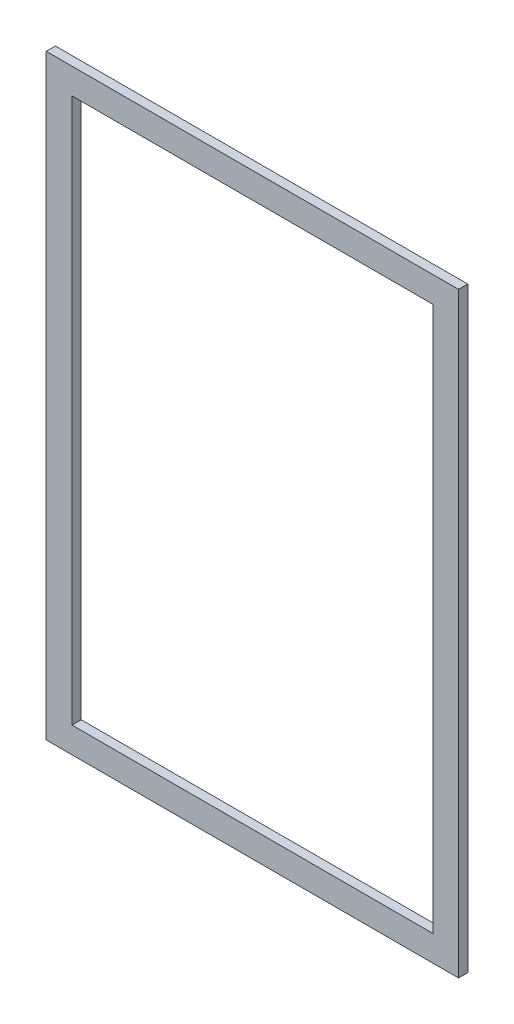
SolidWorks part; units mm, degrees
ref_plane "Front Plane" through (0, 0, 0) normal (0, 0, 1) x (1, 0, 0)
ref_plane "Top Plane" through (0, 0, 0) normal (0, 1, 0) x (1, 0, 0)
ref_plane "Right Plane" through (0, 0, 0) normal (1, 0, 0) x (0, 0, -1)
sketch "Sketch1" plane through (0, 0, 0) normal (0, 0, 1) x (1, 0, 0)
  line L1 (0, 0) -> (224, 0)
  line L2 (0, 0) -> (0, 324)
  line L3 (0, 324) -> (224, 324)
  line L4 (224, 0) -> (224, 324)
  line L6 (14, 14) -> (210, 14)
  line L7 (14, 14) -> (14, 310)
  line L8 (14, 310) -> (210, 310)
  line L9 (210, 14) -> (210, 310)
  dimension "D1" = 14
  dimension "D2" = 210
  dimension "D3" = 224
  dimension "D4" = 14
  dimension "D5" = 310
  dimension "D6" = 324
extrude "Profile" add sketch "Sketch1" along normal blind 5
equation "\"Profile_Depth\" = 5mm"
equation "\"D1@Profile\" = \"Profile_Depth\""
equation "\"Profile_Sketch_1\" = 14mm"
equation "\"D1@Sketch1\" = \"Profile_Sketch_1\""
equation "\"Profile_Sketch_2\" = 210mm"
equation "\"D2@Sketch1\" = \"Profile_Sketch_2\""
equation "\"Profile_Sketch_3\" = 224mm"
equation "\"D3@Sketch1\" = \"Profile_Sketch_3\""
equation "\"Profile_Sketch_4\" = 14mm"
equation "\"D4@Sketch1\" = \"Profile_Sketch_4\""
equation "\"Profile_Sketch_5\" = 310mm"
equation "\"D5@Sketch1\" = \"Profile_Sketch_5\""
equation "\"Profile_Sketch_6\" = 324mm"
equation "\"D6@Sketch1\" = \"Profile_Sketch_6\""
equation "\"EnvelopeWidth\" = 224mm"
equation "\"EnvelopeHeight\" = 324mm"
